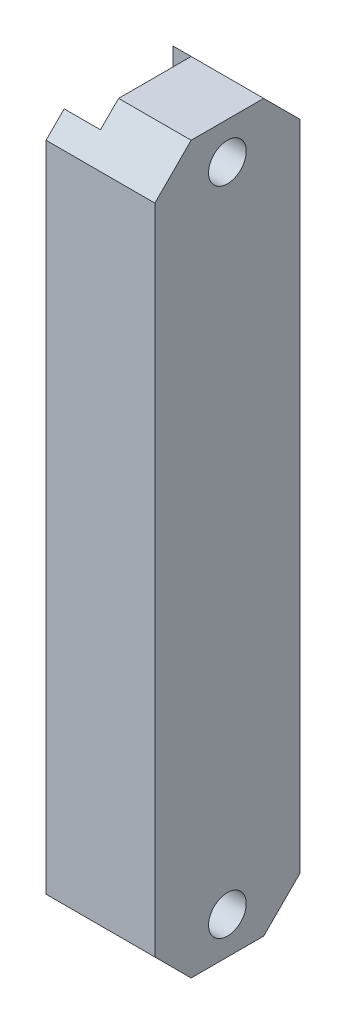
SolidWorks part; units mm, degrees
material "自定义塑料"
ref_plane "前视基准面" through (0, 0, 0) normal (0, 0, 1) x (1, 0, 0)
ref_plane "上视基准面" through (0, 0, 0) normal (0, 1, 0) x (1, 0, 0)
ref_plane "右视基准面" through (0, 0, 0) normal (1, 0, 0) x (0, 0, -1)
sketch "草图1" plane through (0, 0, 0) normal (0, 1, 0) x (1, 0, 0)
  line L0 (-5, 7.5) -> (0, 7.5)
  line L1 (0, 7.5) -> (0, -7.5)
  line L2 (0, -7.5) -> (-5, -7.5)
  line L3 (-5, -7.5) -> (-5, -10)
  line L4 (-5, -10) -> (10, -10)
  line L5 (10, -10) -> (10, 10)
  line L6 (10, 10) -> (-5, 10)
  line L7 (-5, 10) -> (-5, 7.5)
  point P7 (0, 0)
  dimension "D1" = 15
  dimension "D2" = 5
  dimension "D3" = 10
  dimension "D4" = 20
extrude "凸台-拉伸1" add sketch "草图1" along normal blind 100
sketch "草图2" plane through (0, 0, 0) normal (-1, 0, 0) x (0, 0, 1)
  line L0 (0, 100) -> (0, 0) construction
  line L1 (-7.5, 100) -> (7.5, 100) construction
  line L2 (0, 94.9013) -> (44.9013, 50) construction
  line L3 (44.9013, 50) -> (0, 5.0987) construction
  line L4 (-5, 100) -> (-10, 95)
  line L5 (-10, 100) -> (-10, 0) construction
  line L6 (-10, 95) -> (-10, 100)
  line L7 (-10, 100) -> (-5, 100)
  line L8 (10, 100) -> (5, 100)
  line L9 (10, 95) -> (10, 100)
  line L10 (5, 100) -> (10, 95)
  line L11 (-10, 0) -> (-5, 0)
  line L12 (-7.5, 0) -> (7.5, 0) construction
  line L13 (-5, 0) -> (-10, 5)
  line L14 (-10, 5) -> (-10, 0)
  line L15 (10, 5) -> (10, 0)
  line L16 (5, 0) -> (10, 5)
  line L17 (10, 0) -> (5, 0)
  circle A0 centre (0, 94.9013) radius 2.6
  circle A1 centre (0, 5.0987) radius 2.6
  point P11 (0, 50)
  dimension "D1" = 5.2
  dimension "D2" = 63.5
  dimension "D3" = 5
  dimension "D4" = 5
extrude "切除-拉伸1" cut sketch "草图2" against normal through all and the other way through all
